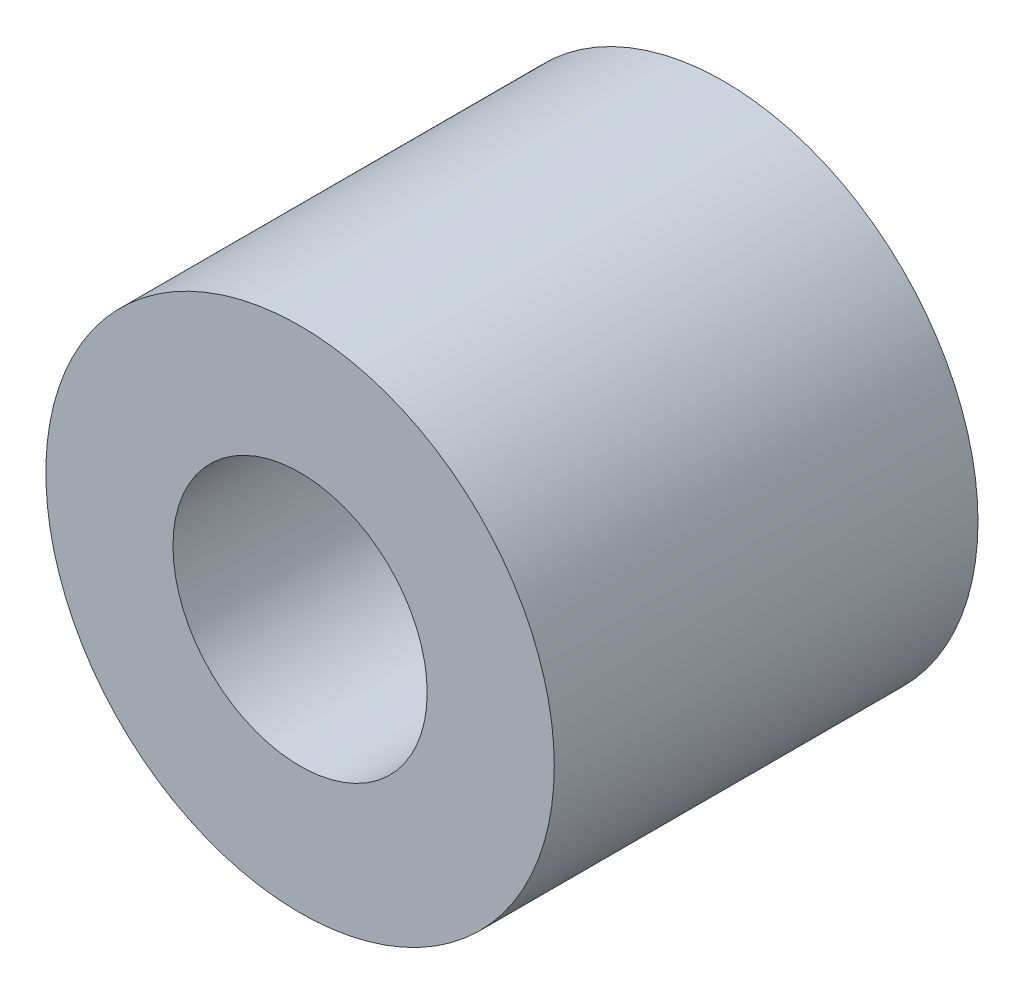
SolidWorks part; units mm, degrees
material "炭素鋼(普通)"
ref_plane "正面" through (0, 0, 0) normal (0, 0, 1) x (1, 0, 0)
ref_plane "平面" through (0, 0, 0) normal (0, 1, 0) x (1, 0, 0)
ref_plane "右側面" through (0, 0, 0) normal (1, 0, 0) x (0, 0, -1)
sketch "ｽｹｯﾁ1" plane through (0, 0, 0) normal (0, 0, 1) x (1, 0, 0)
  circle A0 centre (0, 0) radius 3
  circle A1 centre (0, 0) radius 1.5
  dimension "D1" = 6
  dimension "D2" = 3
extrude "ﾎﾞｽ - 押し出し1" add sketch "ｽｹｯﾁ1" along normal blind 5
